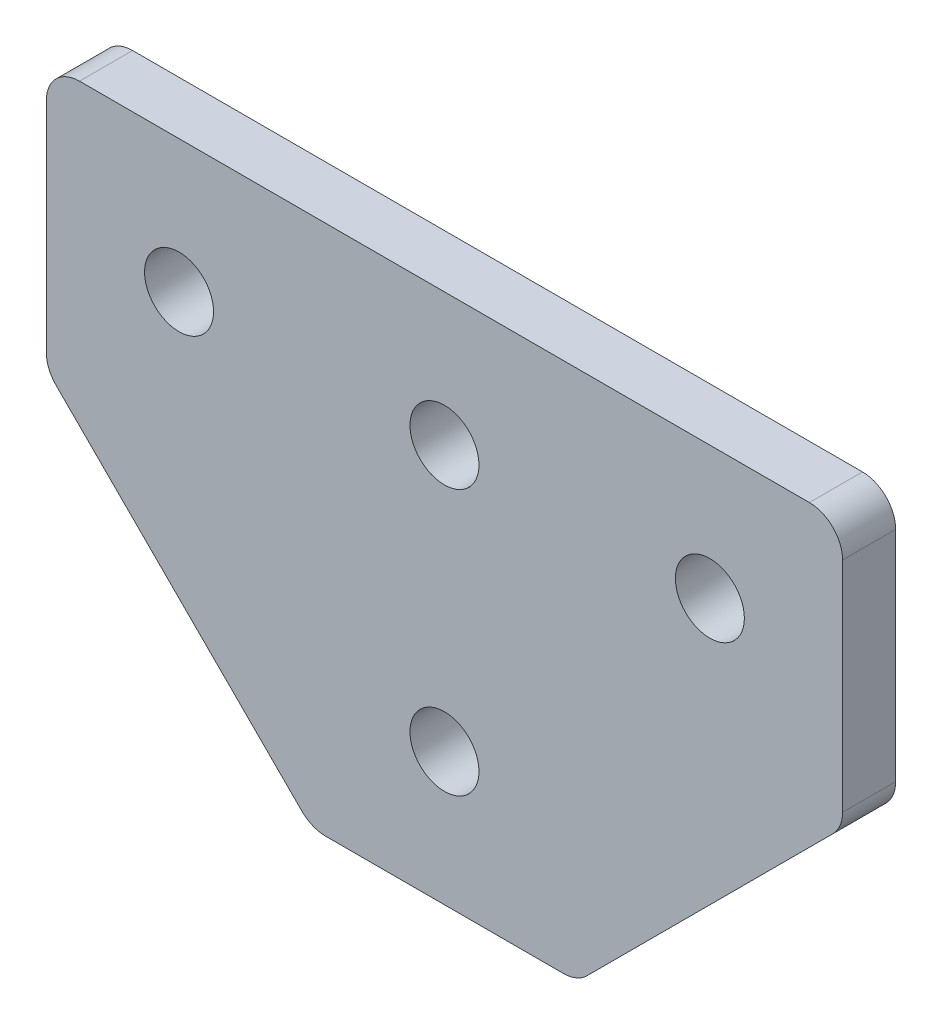
SolidWorks part; units mm, degrees
ref_plane "Спереди" through (0, 0, 0) normal (0, 0, 1) x (1, 0, 0)
ref_plane "Сверху" through (0, 0, 0) normal (0, 1, 0) x (1, 0, 0)
ref_plane "Справа" through (0, 0, 0) normal (1, 0, 0) x (0, 0, -1)
sketch "Эскиз1" plane through (0, 0, 0) normal (0, 0, 1) x (1, 0, 0)
  line L0 (2.5, 0) -> (57.5, 0)
  line L1 (60, -2.5) -> (60, -18.9645)
  line L2 (0, -2.5) -> (0, -18.9645)
  line L3 (0.7322, -20.7322) -> (19.2678, -39.2678)
  line L4 (21.0355, -40) -> (38.9645, -40)
  line L5 (40.7322, -39.2678) -> (59.2678, -20.7322)
  line L6 (10, -10) -> (30, -10) construction
  line L7 (30, -10) -> (30, -30) construction
  circle A0 centre (10, -10) radius 2.6
  circle A1 centre (30, -10) radius 2.6
  circle A2 centre (50, -10) radius 2.6
  circle A3 centre (30, -30) radius 2.6
  arc A4 (0, -18.9645) -> (0.7322, -20.7322) centre (2.5, -18.9645) ccw
  arc A5 (19.2678, -39.2678) -> (21.0355, -40) centre (21.0355, -37.5) ccw
  arc A6 (38.9645, -40) -> (40.7322, -39.2678) centre (38.9645, -37.5) ccw
  arc A7 (60, -18.9645) -> (59.2678, -20.7322) centre (57.5, -18.9645) cw
  arc A8 (57.5, 0) -> (60, -2.5) centre (57.5, -2.5) cw
  arc A9 (2.5, 0) -> (0, -2.5) centre (2.5, -2.5) ccw
  point P21 (0, -20)
  point P24 (20, -40)
  point P27 (40, -40)
  point P30 (60, -20)
  point P33 (60, 0)
  point P36 (0, 0)
  dimension "D8" = 5.2
  dimension "D9" = 10
  dimension "D10" = 10
  dimension "D15" = 2.5
  dimension "D1" = 60
  dimension "D2" = 20
  dimension "D3" = 20
  dimension "D4" = 20
  dimension "D5" = 20
  dimension "D6" = 20
  dimension "D7" = 20
  dimension "D12" = 20
  dimension "D14" = 20
  dimension "D11" = 3
  dimension "D13" = 2
extrude "Бобышка-Вытянуть1" add sketch "Эскиз1" along normal blind 4
